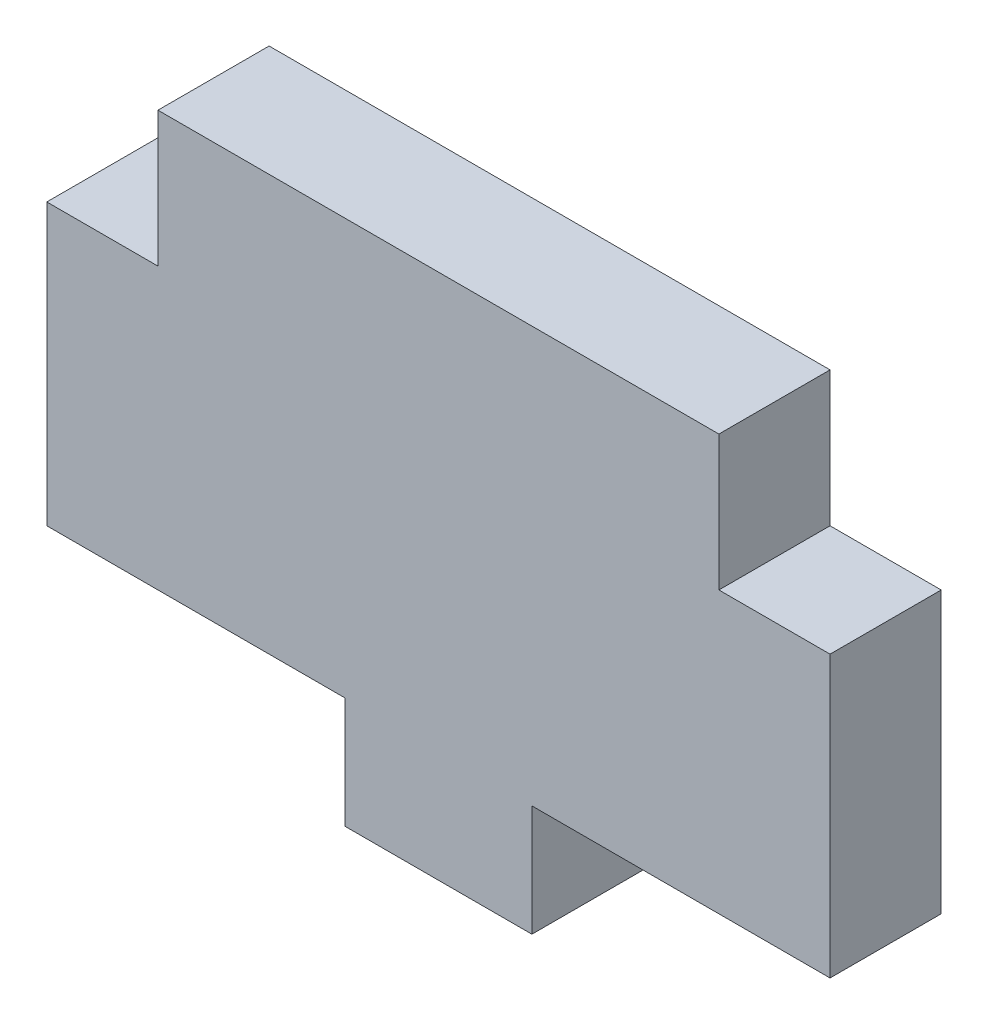
SolidWorks part; units mm, degrees
ref_plane "Front Plane" through (0, 0, 0) normal (0, 0, 1) x (1, 0, 0)
ref_plane "Top Plane" through (0, 0, 0) normal (0, 1, 0) x (1, 0, 0)
ref_plane "Right Plane" through (0, 0, 0) normal (1, 0, 0) x (0, 0, -1)
sketch "Model" plane through (0, 0, 0) normal (0, 0, 1) x (1, 0, 0)
  line L340 (32.35, 25.35) -> (5.35, 25.35)
  line L341 (32.35, 18.85) -> (32.35, 25.35)
  line L342 (37.7, 18.85) -> (32.35, 18.85)
  line L343 (37.7, 5.35) -> (37.7, 18.85)
  line L344 (23.35, 5.35) -> (37.7, 5.35)
  line L345 (23.35, 0) -> (23.35, 5.35)
  line L346 (14.35, 0) -> (23.35, 0)
  line L347 (14.35, 5.35) -> (14.35, 0)
  line L348 (0, 5.35) -> (14.35, 5.35)
  line L349 (0, 18.85) -> (0, 5.35)
  line L350 (5.35, 18.85) -> (0, 18.85)
  line L351 (5.35, 25.35) -> (5.35, 18.85)
extrude "Boss-Extrude1" add sketch "Model" along normal blind 5.35
